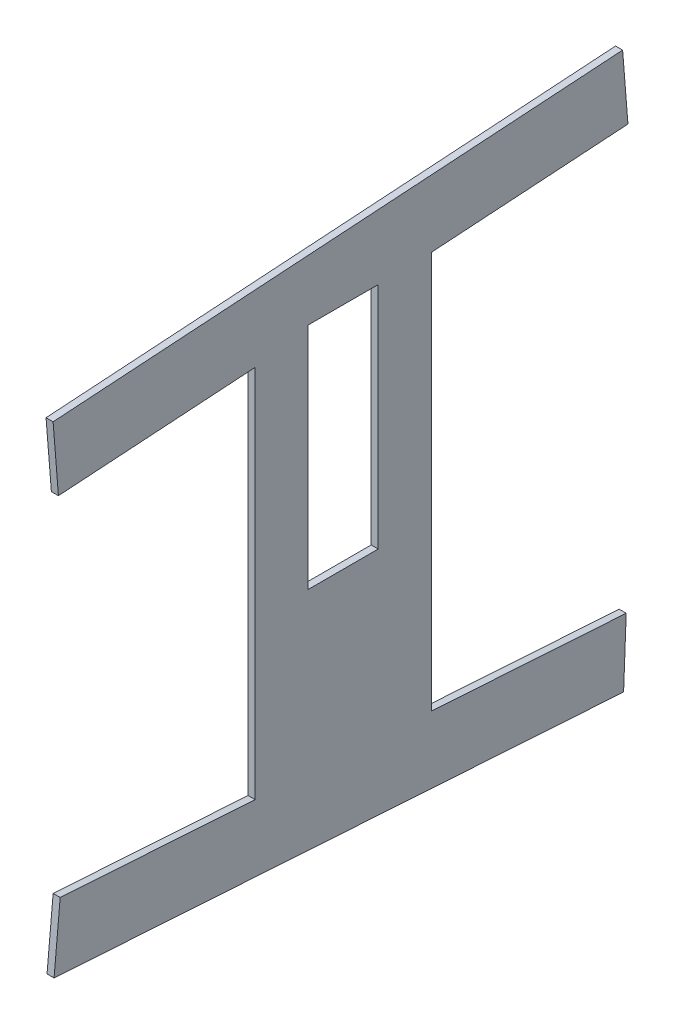
SolidWorks part; units mm, degrees
ref_plane "Front Plane" through (0, 0, 0) normal (0, 0, 1) x (1, 0, 0)
ref_plane "Top Plane" through (0, 0, 0) normal (0, 1, 0) x (1, 0, 0)
ref_plane "Right Plane" through (0, 0, 0) normal (1, 0, 0) x (0, 0, -1)
sketch "Sketch1" plane through (0, 0, 0) normal (1, 0, 0) x (0, 0, -1)
  line L12 (-23.487, -53.1232) -> (-23.487, 53.1192)
  line L13 (-23.487, 53.1192) -> (-79.3154, 49.4796)
  line L14 (-79.3154, 49.4796) -> (-80.8284, 68.4213)
  line L15 (-80.8284, 68.4213) -> (80.8284, 78.9601)
  line L16 (80.8284, 78.9601) -> (82.3414, 60.0184)
  line L17 (82.3414, 60.0184) -> (26.513, 56.3788)
  line L18 (26.513, 56.3788) -> (26.513, -56.3788)
  line L19 (26.513, -56.3788) -> (81.8434, -59.9816)
  line L20 (81.8434, -59.9816) -> (81.1073, -78.9739)
  line L21 (81.1073, -78.9739) -> (-80.5504, -68.4478)
  line L22 (-80.5504, -68.4478) -> (-78.8174, -49.5204)
  line L23 (-78.8174, -49.5204) -> (-23.487, -53.1232)
  point P3 (-98.9164, -68.6006)
  point P13 (0, 73.6907)
  point P14 (0, 0)
  point P15 (26.513, 0)
  dimension "D1" = 19
  dimension "D2" = 19
  dimension "D3" = 99
  dimension "D4" = 120
  dimension "D7" = 50
  dimension "D8" = 162
  dimension "D9" = 162
  dimension "D10" = 89.163
extrude "Boss-Extrude1" add sketch "Sketch1" along normal blind 2
sketch "Sketch2" plane through (2, 0, 0) normal (1, 0, 0) x (0, 0, -1)
  line L1 (-8.5383, 56.0008) -> (11.4617, 56.0008)
  line L2 (-8.5383, 56.0008) -> (-8.5383, -8.9992)
  line L3 (-8.5383, -8.9992) -> (11.4617, -8.9992)
  line L4 (11.4617, 56.0008) -> (11.4617, -8.9992)
  line L5 (-8.5383, 56.0008) -> (11.4617, -8.9992) construction
  line L6 (-8.5383, -8.9992) -> (11.4617, 56.0008) construction
  point P0 (1.4617, 23.5008)
  point P5 (1.7885, 25.3902)
  point P6 (1.6466, 25.7063)
  point P7 (1.7756, 23.8461)
  point P8 (0, 0)
  point P9 (1.4617, 23.4122)
  point P10 (1.5503, 24.6524)
  point P11 (1.4617, 23.5008)
  dimension "D1" = 20
  dimension "D2" = 65
extrude "Cut-Extrude1" cut sketch "Sketch2" against normal through all
